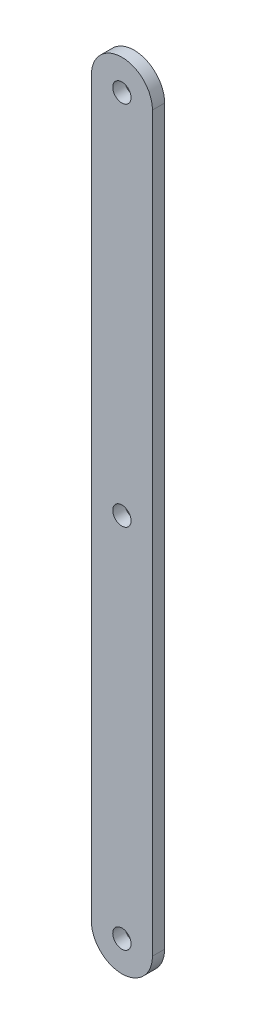
SolidWorks part; units mm, degrees
ref_plane "前视基准面" through (0, 0, 0) normal (0, 0, 1) x (1, 0, 0)
ref_plane "上视基准面" through (0, 0, 0) normal (0, 1, 0) x (1, 0, 0)
ref_plane "右视基准面" through (0, 0, 0) normal (1, 0, 0) x (0, 0, -1)
sketch "草图1" plane through (0, 0, 0) normal (0, 0, 1) x (1, 0, 0)
  line L0 (0, 60) -> (0, -60) construction
  line L1 (5, 60) -> (5, -60)
  line L2 (-5, 60) -> (-5, -60)
  line L3 (55, 0) -> (-55, 0) construction
  arc A0 (5, 60) -> (-5, 60) centre (0, 60) ccw
  arc A1 (-5, -60) -> (5, -60) centre (0, -60) ccw
  circle A2 centre (0, 60) radius 1.5
  circle A3 centre (0, -60) radius 1.5
  circle A5 centre (0, 0) radius 1.5
  point P3 (0, 0)
  dimension "D3" = 3
  dimension "D4" = 60
  dimension "D5" = 3
  dimension "D1" = 60
  dimension "D2" = 10
extrude "凸台-拉伸1" add sketch "草图1" along normal blind 2
